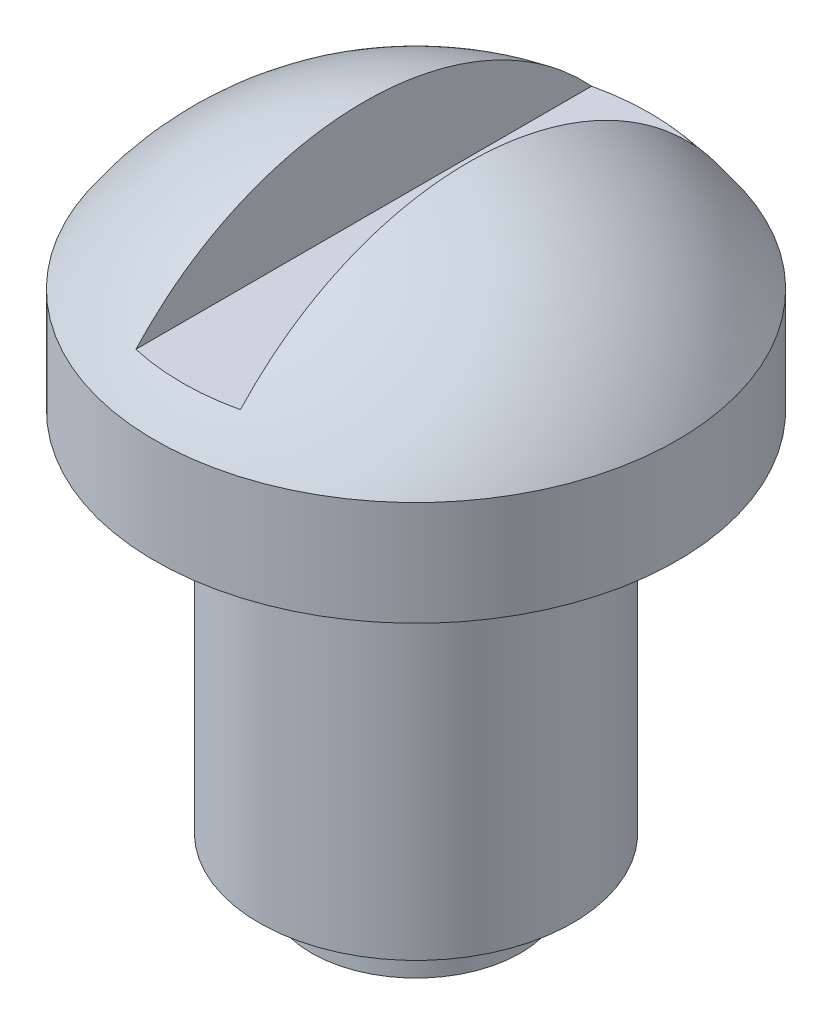
SolidWorks part; units mm, degrees
ref_plane "Front Plane" through (0, 0, 0) normal (0, 0, 1) x (1, 0, 0)
ref_plane "Top Plane" through (0, 0, 0) normal (0, 1, 0) x (1, 0, 0)
ref_plane "Right Plane" through (0, 0, 0) normal (1, 0, 0) x (0, 0, -1)
sketch "Sketch1" plane through (0, 0, 0) normal (0, 0, 1) x (1, 0, 0)
  line L0 (0, 0) -> (0, -12.6834)
  line L1 (0, -12.6834) -> (2, -12.6834)
  line L2 (2, -12.6834) -> (2, -11.6834)
  line L3 (2, -11.6834) -> (3, -11.6834)
  line L4 (3, -11.6834) -> (3, -4.6834)
  line L5 (3, -4.6834) -> (5, -4.6834)
  line L6 (5, -4.6834) -> (5, -2.6834)
  arc A0 (0, 0) -> (5, -2.6834) centre (0, -6) cw
  point P10 (0, 0)
  point P11 (0, 0)
  point P12 (0, 0)
  point P13 (0, 0)
  dimension "D7" = 6
  dimension "D1" = 2
  dimension "D2" = 1
  dimension "D3" = 7
  dimension "D4" = 2
  dimension "D5" = 3
  dimension "D6" = 5
revolve "Revolve1" add sketch "Sketch1" angle 360 about L0
sketch "Sketch2" plane through (0, 0, 0) normal (0, 0, 1) x (1, 0, 0)
  line L1 (-1, 2) -> (1, 2)
  line L2 (-1, 2) -> (-1, -2)
  line L3 (-1, -2) -> (1, -2)
  line L4 (1, 2) -> (1, -2)
  line L5 (-1, 2) -> (1, -2) construction
  line L6 (-1, -2) -> (1, 2) construction
  point P0 (0, 0)
  dimension "D1" = 2
  dimension "D2" = 2
extrude "Cut-Extrude1" cut sketch "Sketch2" against normal mid plane 10
